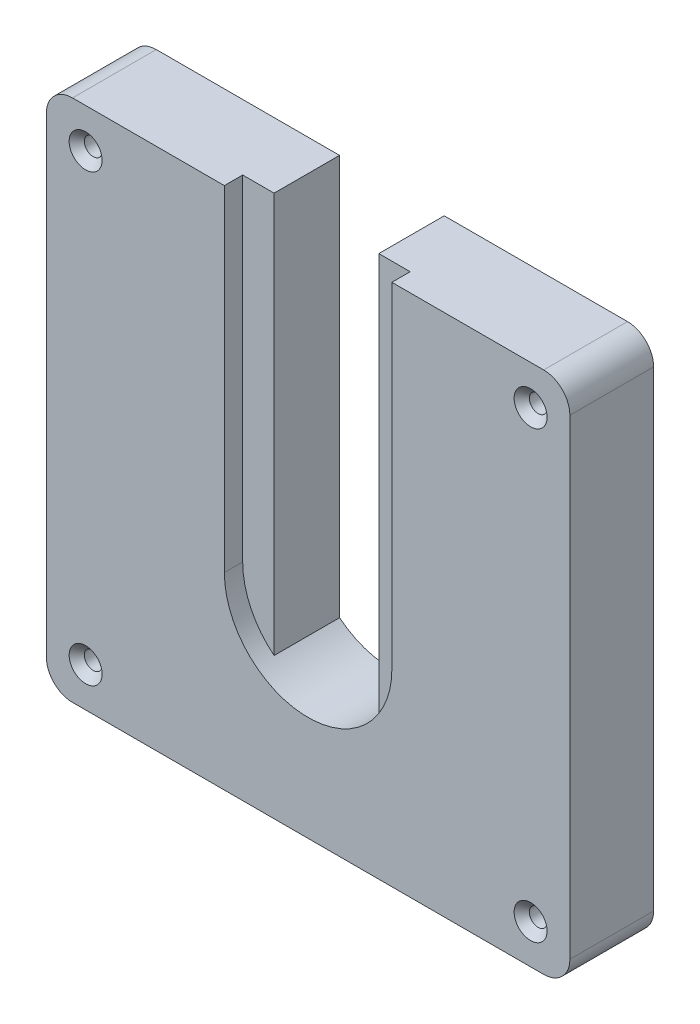
SolidWorks part; units mm, degrees
ref_plane "Front Plane" through (0, 0, 0) normal (0, 0, 1) x (1, 0, 0)
ref_plane "Top Plane" through (0, 0, 0) normal (0, 1, 0) x (1, 0, 0)
ref_plane "Right Plane" through (0, 0, 0) normal (1, 0, 0) x (0, 0, -1)
sketch "Sketch1" plane through (0, 0, 0) normal (0, 0, 1) x (1, 0, 0)
  line L0 (-50, 50) -> (50, -50) construction
  line L1 (-50, -50) -> (50, -50)
  line L2 (-50, -50) -> (-50, 50)
  line L3 (-50, 50) -> (50, 50)
  line L4 (50, -50) -> (50, 50)
  dimension "D1" = 100
  dimension "D2" = 100
extrude "Boss-Extrude1" add sketch "Sketch1" along normal blind 16 contours L4 L3 L2 L1
sketch "Sketch2" plane through (0, 0, 16) normal (0, 0, 1) x (1, 0, 0)
  line L4 (-50, -50) -> (50, -50)
  line L5 (50, -50) -> (50, 50)
  line L6 (50, 50) -> (-50, 50)
  line L7 (-50, 50) -> (-50, -50)
  line L8 (-50, -50) -> (50, -50)
  line L9 (50, -50) -> (50, 50)
  line L10 (50, 50) -> (-50, 50)
  line L11 (-50, 50) -> (-50, -50)
  dimension "D1" = 0
extrude "Boss-Extrude2" add sketch "Sketch2" along normal blind 16 separate body
sketch "Sketch3" plane through (0, 50, 0) normal (0, 1, 0) x (1, 0, 0)
  line L21 (-16, -32) -> (-16, -28.5)
  line L23 (50, -32) -> (-50, -32) construction
  line L24 (-16, -28.5) -> (-10, -28.5)
  line L25 (-10, -28.5) -> (-10, -16)
  line L26 (-10, -16) -> (-16, -16)
  line L27 (-16, -16) -> (-16, -11)
  line L28 (-16, -11) -> (16, -11)
  line L29 (-16, -32) -> (16, -32)
  line L30 (0, -32) -> (0, 0) construction
  line L31 (16, -16) -> (16, -11)
  line L32 (10, -16) -> (16, -16)
  line L33 (10, -28.5) -> (10, -16)
  line L34 (16, -28.5) -> (10, -28.5)
  line L35 (16, -32) -> (16, -28.5)
  point P17 (0, -11)
  dimension "D1" = 3.5
  dimension "D2" = 12.5
  dimension "D3" = 5
  dimension "D4" = 32
  dimension "D5" = 32
  dimension "D6" = 20
extrude "Cut-Extrude1" cut sketch "Sketch3" against normal blind 80
sketch "Sketch4" plane through (0, 0, 32) normal (0, 0, 1) x (1, 0, 0)
  line L0 (-16, -30) -> (16, -30) construction
  line L9 (-16, -30) -> (-16, 50)
  line L10 (-16, 50) -> (-50, 50)
  line L11 (-50, 50) -> (-50, -50)
  line L12 (-50, -50) -> (50, -50)
  line L13 (50, -50) -> (50, 50)
  line L14 (50, 50) -> (16, 50)
  line L15 (16, 50) -> (16, -30)
  line L16 (16, -30) -> (-16, -30)
  line L17 (-16, -30) -> (-16, -14)
  line L23 (16, -14) -> (16, -30)
  line L24 (16, -30) -> (-16, -30)
  arc A0 (-16, -14) -> (16, -14) centre (0, -14) ccw
  line M10 (-16, -30) -> (-16, 50)
  line M16 (16, 50) -> (16, -30)
  line M17 (16, -30) -> (-16, -30)
  dimension "D1" = 0
extrude "Boss-Extrude3" add sketch "Sketch4" against normal blind 16 contours A0 L24 M10 | A0 M17 M16
sketch "Sketch5" plane through (0, 0, 11) normal (0, 0, 1) x (1, 0, 0)
  line L7 (16, 50) -> (-16, 50)
  line L8 (-16, 50) -> (-16, -30)
  line L9 (-16, -30) -> (16, -30)
  line L10 (16, -30) -> (16, 50)
  line L12 (-16, -14) -> (-16, -30)
  line L13 (-16, -30) -> (16, -30)
  line L14 (16, -30) -> (16, -14)
  arc A1 (-16, -14) -> (16, -14) centre (0, -14) ccw construction
  arc A2 (-16, -14) -> (16, -14) centre (0, -14) ccw
  line M6 (-16, 50) -> (-16, -30)
  line M7 (-16, -30) -> (16, -30)
  line M8 (16, -30) -> (16, 50)
  dimension "D1" = 0
extrude "Boss-Extrude4" add sketch "Sketch5" along normal up to body separate body contours A2 L13 M8 | A2 M6 M7
hole_wizard "CSK for M3 Countersunk Flat Head Screw1" positions "Sketch6" profile "Sketch7" countersink size "M3" standard "ISO" end condition through all
sketch "Sketch6" plane through (0, 0, 32) normal (0, 0, 1) x (1, 0, 0)
  line L1 (-42.5, 42.5) -> (42.5, 42.5)
  line L2 (-42.5, 42.5) -> (-42.5, -42.5)
  line L3 (-42.5, -42.5) -> (42.5, -42.5)
  line L4 (42.5, 42.5) -> (42.5, -42.5)
  line L5 (0, 42.5) -> (0, 0) construction
  line L6 (0, 0) -> (42.5, 0) construction
  line L8 (-50, 50) -> (-50, -50) construction
  line L9 (-16, 50) -> (-50, 50) construction
  point P0 (-42.5, 42.5)
  point P2 (42.5, 42.5)
  point P4 (42.5, -42.5)
  point P6 (-42.5, -42.5)
  dimension "D1" = 7.5
  dimension "D2" = 7.5
sketch "Sketch7" plane through (-42.5, 42.5, 32) normal (1, 0, 0) x (0, -1, 0)
  line L0 (0, 0) -> (0, 32)
  line L1 (0, 32) -> (1.7, 32)
  line L2 (1.7, 32) -> (1.7, 1.45)
  line L3 (1.7, 1.45) -> (3.15, 0)
  line L5 (3.15, 0) -> (0, 0)
  line L6 (-1.7, 1.45) -> (-3.15, 0) construction
  line L11 (0, -6.35) -> (0, 107.95) construction
  dimension "Thru Hole Dia." = 3.4
  dimension "Thru Hole Depth" = 32
  dimension "Near C'Sink Dia." = 6.3
  dimension "Near C'Sink Angle" = 90
fillet "Fillet1" radius 5 4 edges at (-50, -50, 24) (50, -50, 24) (50, 50, 24) (-50, 50, 24)
fillet "Fillet2" radius 5 4 edges at (50, -50, 8) (50, 50, 8) (-50, 50, 8) (-50, -50, 8)
delete or keep bodies "Body-Delete/Keep 1" [suppressed] type keep bodies bodies 112
delete or keep bodies "Body-Delete/Keep 2" type keep bodies bodies 111
